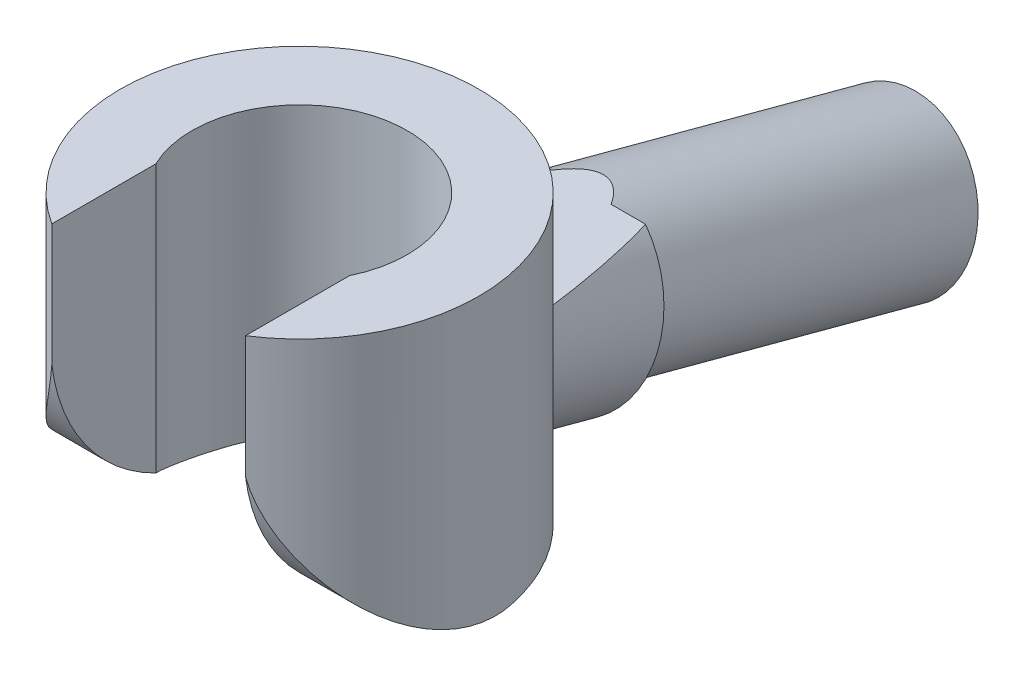
SolidWorks part; units mm, degrees
ref_plane "Front Plane" through (0, 0, 0) normal (0, 0, 1) x (1, 0, 0)
ref_plane "Top Plane" through (0, 0, 0) normal (0, 1, 0) x (1, 0, 0)
ref_plane "Right Plane" through (0, 0, 0) normal (1, 0, 0) x (0, 0, -1)
sketch "Sketch1" plane through (0, 0, 0) normal (0, 1, 0) x (1, 0, 0)
  circle A0 centre (0, 0) radius 1.5
  circle A1 centre (0, 0) radius 2.5
  dimension "D1" = 3
  dimension "D2" = 5
extrude "Boss-Extrude1" add sketch "Sketch1" along normal blind 4
sketch "Sketch2" plane through (0, 4, 0) normal (0, 1, 0) x (1, 0, 0)
  line L0 (-1.35, 0) -> (1.35, 0)
  line L1 (1.35, 0) -> (1.35, -3.1542)
  line L2 (1.35, -3.1542) -> (-1.35, -3.1542)
  line L3 (-1.35, -3.1542) -> (-1.35, 0)
  line L4 (0, 0.7457) -> (0, -3.6603) construction
  dimension "D1" = 2.7
  dimension "D2" = 1.35
  dimension "D3" = 3.1542
extrude "Cut-Extrude1" cut sketch "Sketch2" against normal through all
ref_plane "Plane1" through (5, 0, 0) normal (1, 0, 0) x (0, 0, -1)
sketch "Sketch3" plane through (5, 0, 0) normal (1, 0, 0) x (0, 0, -1)
  line L0 (-2.1042, 4) -> (-2.1042, 0) construction
  line L1 (-2.1042, 0) -> (2.5, 0) construction
  line L2 (-2.1042, 2.3) -> (-2.1042, 0)
  line L3 (-2.1042, 0) -> (0.5, 0)
  arc A0 (-2.1042, 2.3) -> (0.5, 0) centre (0.5, 2.6243) ccw
  dimension "D1" = 1.7
  dimension "D2" = 2
extrude "Cut-Extrude2" cut sketch "Sketch3" against normal through all
sketch "Sketch4" plane through (0, 0, 0) normal (1, 0, 0) x (0, 0, -1)
  line L0 (2.5, 1.4) -> (8.2956, -0.1529)
  line L1 (2.5, 0) -> (2.5, 4) construction
  line L2 (0.5, 0) -> (2.5, 0) construction
  dimension "D1" = 75
  dimension "D2" = 1.4
  dimension "D3" = 6
ref_plane "Plane2" through (0, -0.1529, -8.2956) normal (0, -0.2588, -0.9659) x (-1, 0, 0)
sketch "Sketch5" plane through (0, -0.1529, -8.2956) normal (0, -0.2588, -0.9659) x (-1, 0, 0)
  circle A2 centre (0, 0) radius 1.125
  dimension "D1" = 2.25
extrude "Boss-Extrude2" add sketch "Sketch5" against normal up to next contours A2
sketch "Sketch6" plane through (0, -0.1529, -8.2956) normal (0, -0.2588, -0.9659) x (-1, 0, 0)
  circle A0 centre (0, 0) radius 1.375
  dimension "D1" = 2.75
extrude "Boss-Extrude3" add sketch "Sketch6" against normal up to surface (1.5684 mm away) from offset 4.8 offset against normal yes
ref_plane "Plane3" through (0, 0, -10) normal (0, 0, 1) x (1, 0, 0)
sketch "Sketch7" plane through (0, 0, -10) normal (0, 0, 1) x (1, 0, 0)
  line L0 (0, -2.7534) -> (0, 3.7471) construction
  line L1 (0, 4.0198) -> (-2.1301, 4.0198)
  line L2 (-2.1301, 4.0198) -> (-2.1301, 2.1)
  line L3 (-2.1301, 2.1) -> (2.08, 2.1)
  line L4 (2.08, 2.1) -> (2.08, 4.0198)
  line L5 (2.08, 4.0198) -> (0, 4.0198)
  line L6 (2.5, 4) -> (-2.5, 4) construction
  dimension "D1" = 4.2102
  dimension "D2" = 1.9198
  dimension "D3" = 1.9
  dimension "D4" = 2.08
extrude "Cut-Extrude3" cut sketch "Sketch7" along normal up to surface (8.6131 mm away)
